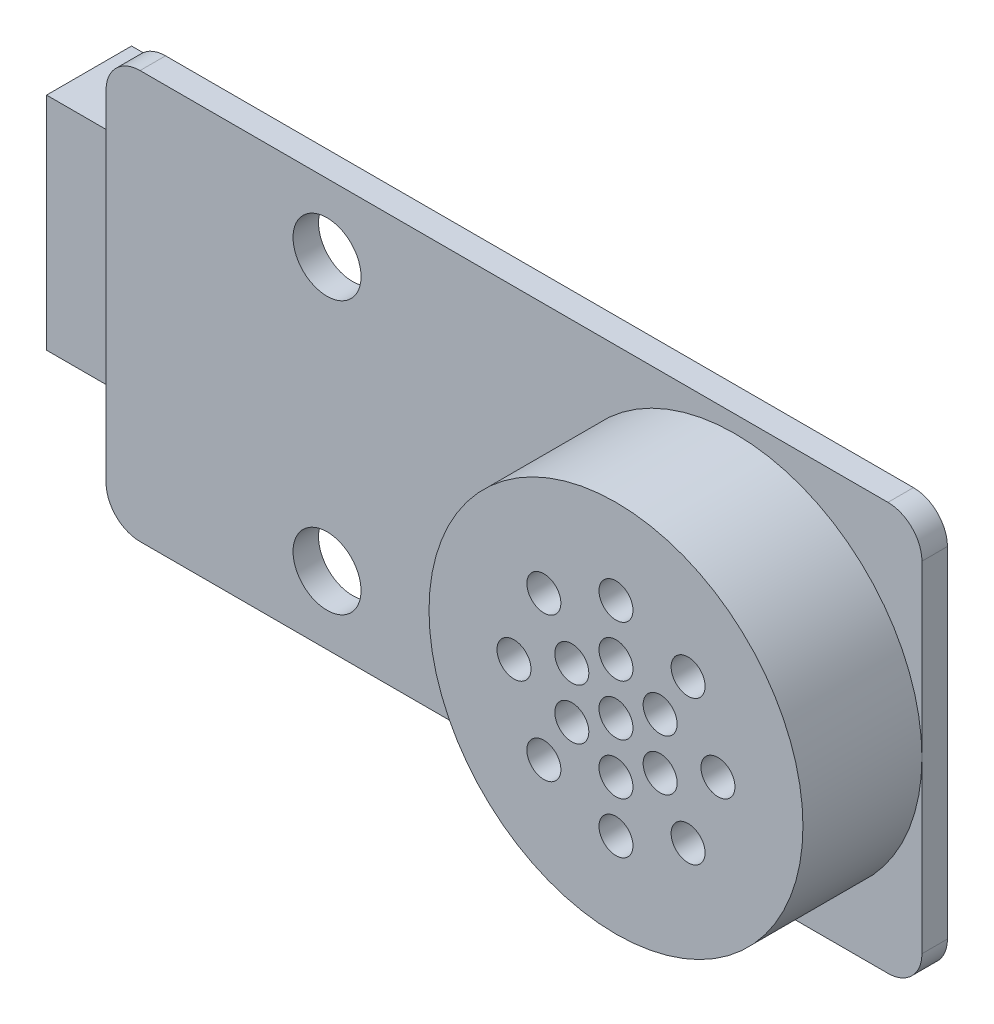
SolidWorks part; units mm, degrees
material "AISI 304"
ref_plane "前视基准面" through (0, 0, 0) normal (0, 0, 1) x (1, 0, 0)
ref_plane "上视基准面" through (0, 0, 0) normal (0, 1, 0) x (1, 0, 0)
ref_plane "右视基准面" through (0, 0, 0) normal (1, 0, 0) x (0, 0, -1)
other "Configuration Table"
sketch "草图1" plane through (0, 0, 0) normal (0, 0, 1) x (1, 0, 0)
  line L1 (-24, -12) -> (24, -12)
  line L2 (-24, -12) -> (-24, 12)
  line L3 (-24, 12) -> (24, 12)
  line L4 (24, -12) -> (24, 12)
  line L5 (-24, -12) -> (24, 12) construction
  line L6 (-24, 12) -> (24, -12) construction
  point P0 (0, 0)
  dimension "D1" = 48
  dimension "D2" = 24
extrude "凸台-拉伸1" add sketch "草图1" along normal blind 1.5
fillet "圆角1" radius 2 4 edges at (-24, -12, 0.75) (24, -12, 0.75) (24, 12, 0.75) (-24, 12, 0.75)
sketch "草图2" plane through (0, 0, 1.5) normal (0, 0, 1) x (1, 0, 0)
  line L0 (0, 0) -> (13, 0) construction
  line L1 (24, -10) -> (24, 10) construction
  circle A0 centre (13, 0) radius 11
  dimension "D1" = 22
extrude "凸台-拉伸2" add sketch "草图2" along normal blind 7
sketch "草图3" plane through (0, 0, 0) normal (0, 0, -1) x (-1, 0, 0)
  line L0 (0, 0) -> (23.5, 0) construction
  line L1 (18, -6.5) -> (29, -6.5)
  line L2 (18, -6.5) -> (18, 6.5)
  line L3 (18, 6.5) -> (29, 6.5)
  line L4 (29, -6.5) -> (29, 6.5)
  line L5 (18, -6.5) -> (29, 6.5) construction
  line L6 (18, 6.5) -> (29, -6.5) construction
  line L7 (24, 10) -> (24, -10) construction
  point P0 (23.5, 0)
  dimension "D1" = 13
  dimension "D2" = 11
  dimension "D3" = 6
extrude "凸台-拉伸3" add sketch "草图3" along normal blind 5
sketch "草图4" plane through (0, 0, 1.5) normal (0, 0, 1) x (1, 0, 0)
  line L0 (0, 0) -> (-24, 0) construction
  line L1 (-24, 6.5) -> (-24, -6.5) construction
  line L2 (-24, 10) -> (-24, -10) construction
  circle A0 centre (-11, 8) radius 2
  circle A1 centre (-11, -8) radius 2
  dimension "D1" = 4
  dimension "D2" = 16
  dimension "D3" = 13
extrude "切除-拉伸1" cut sketch "草图4" against normal blind 5
sketch "草图5" plane through (0, 0, 8.5) normal (0, 0, 1) x (1, 0, 0)
  line L0 (13, 3) -> (13, 0) construction
  line L1 (13, 6) -> (13, 0) construction
  circle A0 centre (13, 0) radius 1
  circle A1 centre (13, 3) radius 1
  circle A2 centre (7, 0) radius 1
  circle A3 centre (15.5981, 1.5) radius 1
  circle A4 centre (15.5981, -1.5) radius 1
  circle A5 centre (13, -3) radius 1
  circle A6 centre (10.4019, -1.5) radius 1
  circle A7 centre (10.4019, 1.5) radius 1
  circle A8 centre (8.7574, 4.2426) radius 1
  circle A9 centre (13, 6) radius 1
  circle A10 centre (17.2426, 4.2426) radius 1
  circle A11 centre (19, 0) radius 1
  circle A12 centre (17.2426, -4.2426) radius 1
  circle A13 centre (13, -6) radius 1
  circle A14 centre (8.7574, -4.2426) radius 1
  point P19 (13, 0)
  point P34 (13, 0)
  dimension "D1" = 2
  dimension "D2" = 6
  dimension "D3" = 3
  dimension "D4" = 8
  dimension "D5" = 6
extrude "切除-拉伸2" cut sketch "草图5" against normal up to surface (7 mm away) up to face at (-9, 8, 1.5)
